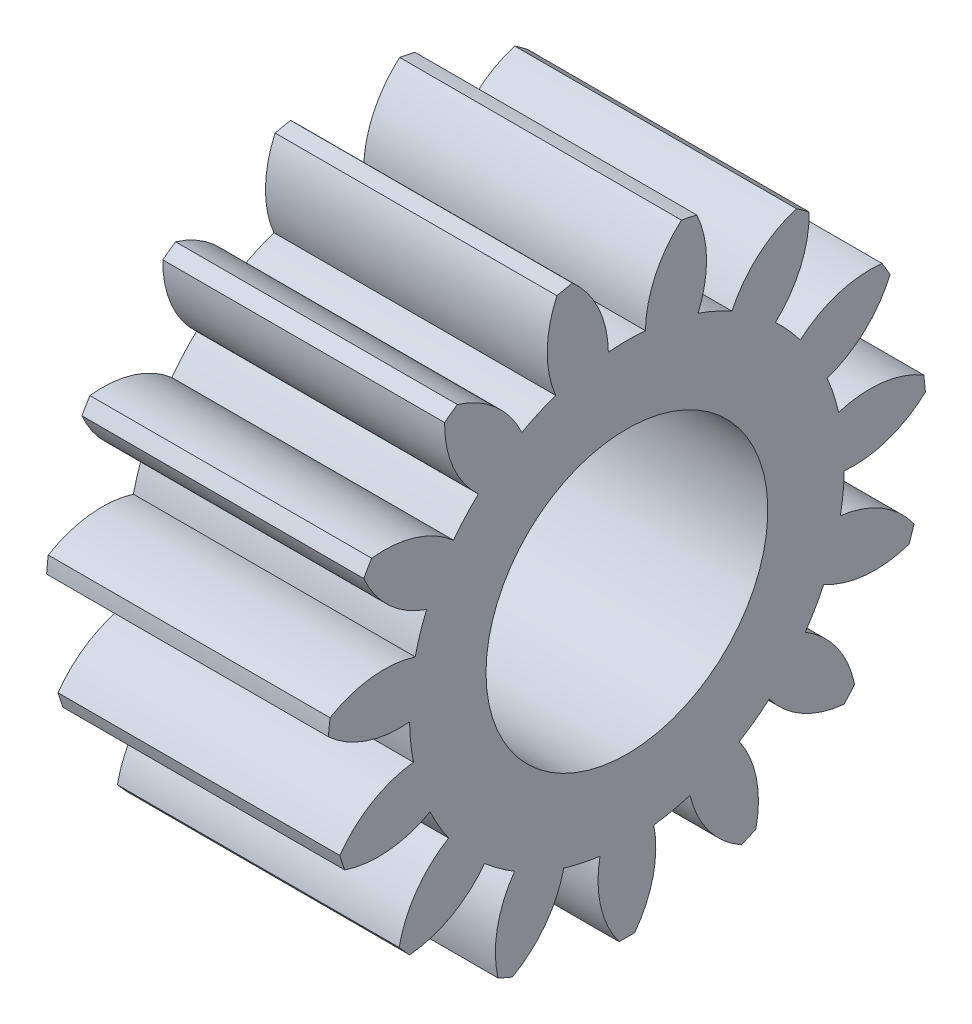
SolidWorks part; units mm, degrees
ref_plane "Plane1" through (0, 0, 0) normal (0, 0, 1) x (1, 0, 0)
ref_plane "Plane2" through (0, 0, 0) normal (0, 1, 0) x (1, 0, 0)
ref_plane "Plane3" through (0, 0, 0) normal (1, 0, 0) x (0, 0, -1)
sketch "HoldingSke" plane through (0, 0, 0) normal (0, 1, 0) x (1, 0, 0)
  line L0 (0, 0) -> (1570.209, -420.7362)
  line L1 (-15, 0) -> (100, 0) construction
  line L2 (0, 0) -> (-2.1039, 2.3779)
  line L3 (0, 0) -> (-11.863, 4.5341)
  line L4 (0, 0) -> (8.3417, 2.2352)
  line L5 (0, 0) -> (-47.5972, -17.7524)
  line L6 (0, 0) -> (-2.632, -1.7758)
  line L7 (-2.1039, 2.3779) -> (8.8308, 51.9871)
  line L8 (-76.2, 54.61) -> (-72.771, 54.61)
  line L9 (-71.009, 38.7566) -> (-53.1078, 45.2721)
  line L10 (-76.2, 71.12) -> (104.1128, 71.12)
  line L11 (0, 0) -> (-3.175, 0)
  line L12 (-76.2, 101.6) -> (-76.1858, 101.6)
  line L13 (24.9733, 27.94) -> (52.9518, 28.4284)
  line L14 (24.9733, 27.94) -> (25.0241, 27.9398)
  line L15 (24.9733, 27.94) -> (100.4021, 29.52)
  circle A0 centre (0, 0) radius 1.5875
  circle A1 centre (0, 0) radius 2.4495
  circle A2 centre (0, 0) radius 38.1
  circle A3 centre (0, 0) radius 1.5875
  dimension "MHD" = 4.899
  dimension "Hub_dia" = 76.2
  dimension "Bore" = 3.175
  dimension "MBD" = 3.175
  dimension "Num_teeth" = 15
  dimension "Pitch" = 1625.6
  dimension "Overall_len" = 50.8
  dimension "Show_teeth" = 15
  dimension "Thickness" = 3.175
  dimension "OAL" = 50.8001
  dimension "T_dim" = 3.429
  dimension "Ap" = 20
  dimension "H" = 19.05
  dimension "Pitch_radius" = 180.3128
  dimension "Width" = 3.175
  dimension "Backlash" = 0.0142
  dimension "Addendum_fac" = 1
  dimension "Dedendum_fac" = 1.2
  dimension "Clearance_fac" = 0.2
  dimension "Dedendum_add" = 0.0508
sketch "BasProSke" plane through (0, 0, 0) normal (0, 1, 0) x (1, 0, 0)
  line L0 (-10, 0) -> (60, 0) construction
  line L1 (0, 0) -> (0, 3.3734)
  line L2 (0, 0) -> (3.175, 0)
  line L3 (3.175, 0) -> (3.175, 3.3734)
  line L4 (3.175, 3.3734) -> (0, 3.3734)
  dimension "Thickness" = 3.175
  dimension "Diameter" = 6.7469
revolve "Base-Revolve" add sketch "BasProSke" angle 360 about L0
sketch "TooCutSke" plane through (0, 0, 0) normal (1, 0, 0) x (0, 0, -1)
  line L1 (0, 0) -> (0, 107) construction
  line L2 (0, 0) -> (-0.336, 2.9575) construction
  line L3 (0, 0) -> (-1.232, 5.796) construction
  line L4 (-0.336, 2.9575) -> (-0.616, 2.898) construction
  arc A0 (0.2088, 2.4406) -> (-0.2088, 2.4406) centre (0, 0) ccw
  arc A1 (0.6391, 3.3382) -> (-0.6391, 3.3382) centre (0, 0) ccw
  circle A2 centre (0, 0) radius 2.9766 construction
  circle A3 centre (0, 0) radius 2.7971 construction
  arc A4 (-0.2088, 2.4406) -> (-0.6391, 3.3382) centre (-1.3993, 2.4219) ccw
  arc A5 (0.6391, 3.3382) -> (0.2088, 2.4406) centre (1.3993, 2.4219) ccw
  dimension "Root_dia" = 4.899
  dimension "Overcut_dia" = 6.7977
  dimension "Pitch_dia" = 5.9531
  dimension "Base_dia" = 5.5941
  dimension "Flank_rad" = 1.1906
  dimension "Half_ang" = 12
  dimension "Half_CT" = 0.2862
extrude "ToothCut" cut sketch "TooCutSke" along normal through all
fillet "Breaks" [suppressed] radius 0.0079
fillet "RootFillets" [suppressed] radius 0.1302
pattern_circular "TeethCuts" count 15 every 24 about axis through (-10, 0, 0) along (1, 0, 0) of "ToothCut", "RootFillets", "Breaks"
sketch "HubNeaOneSke" plane through (0, 0, 0) normal (-1, 0, 0) x (0, 0, 1)
  circle A0 centre (0, 0) radius 2.4495
  dimension "Diameter" = 4.899
extrude "HubNearOne" [suppressed] add sketch "HubNeaOneSke" along normal blind 47.6251
sketch "HubNeaBotSke" plane through (0, 0, 0) normal (-1, 0, 0) x (0, 0, 1)
  circle A0 centre (0, 0) radius 2.4495
  dimension "Diameter" = 4.899
extrude "HubNearBoth" [suppressed] add sketch "HubNeaBotSke" along normal blind 23.8125
ref_plane "FarPln" through (3.175, 0, 0) normal (1, 0, 0) x (0, 0, -1)
sketch "HubFarSke" plane through (3.175, 0, 0) normal (1, 0, 0) x (0, 0, -1)
  circle A0 centre (0, 0) radius 2.4495
  dimension "Diameter" = 4.899
extrude "HubFar" [suppressed] add sketch "HubFarSke" along normal blind 23.8125
sketch "BorSke" plane through (0, 0, 0) normal (1, 0, 0) x (0, 0, -1)
  circle A0 centre (0, 0) radius 1.5875
  dimension "Diameter" = 3.175
extrude "Bore" cut sketch "BorSke" along normal mid plane 101.6001
sketch "KeySke" plane through (0, 0, 0) normal (1, 0, 0) x (0, 0, -1)
  line L0 (-0.127, 0) -> (-0.127, 1.8415)
  line L1 (-0.127, 1.8415) -> (0.127, 1.8415)
  line L2 (0.127, 1.8415) -> (0.127, 0)
  line L3 (0, 0) -> (0, 34) construction
  line L4 (-0.127, 0) -> (0.127, 0)
  dimension "Offset" = 1.8415
  dimension "Width" = 0.254
extrude "Keyway" [suppressed] cut sketch "KeySke" along normal mid plane 101.6001
pattern_circular "Keyway2" [suppressed] count 2 every 90 about axis through (-10, 0, 0) along (1, 0, 0)
equation "' \"Pitch@HoldingSke\" = 4"
equation "' \"Num_teeth@HoldingSke\" = 12"
equation "' \"Ap@HoldingSke\" =  20"
equation "' \"Ap@HoldingSke\" = 20"
equation "' \"Width@HoldingSke\" = 0.5"
equation "' \"Hub_dia@HoldingSke\"= 1"
equation "' \"Hub_dia@HoldingSke\" = 1"
equation "' \"Overall_len@HoldingSke\" = 1.0"
equation "' \"Bore@HoldingSke\" = 0.75"
equation "' \"T_dim@HoldingSke\" = 0.85"
equation "' \"Width@KeySke\" = 0.25"
equation "' \"Show_teeth@HoldingSke\" = 13"
equation "' \"Backlash@HoldingSke\" = 0.009"
equation "' \"Addendum_fac@HoldingSke\" = 1.0"
equation "' \"Dedendum_fac@HoldingSke\" = 1.25"
equation "' \"Dedendum_add@HoldingSke\" = 0.00005"
equation "' \"Clearance_fac@HoldingSke\" = 0.25"
equation "' \"Pitch@HoldingSke\" = 0.5"
equation "' \"Num_teeth@HoldingSke\" = 23"
equation "' \"Show_teeth@HoldingSke\" = 23"
equation "' \"Backlash@HoldingSke\" = 0.0375"
equation "\"Overcut_dia@TooCutSke\" = (\"Num_teeth@HoldingSke\" + 2 * \"Addendum_fac@HoldingSke\") / \"Pitch@HoldingSke\" + 0.002"
equation "\"Pitch_dia@TooCutSke\" = \"Num_teeth@HoldingSke\" / \"Pitch@HoldingSke\""
equation "\"Base_dia@TooCutSke\" = \"Num_teeth@HoldingSke\" / \"Pitch@HoldingSke\" * cos((\"Ap@HoldingSke\"  * 3.14159265 / 180))"
equation "\"Root_dia@TooCutSke\" = (\"Num_teeth@HoldingSke\" + 2) / \"Pitch@HoldingSke\" - 2 * (\"Addendum_fac@HoldingSke\" + \"Dedendum_fac@HoldingSke\") / \"Pitch@HoldingSke\" - \"Dedendum_add@HoldingSke\" * 2"
equation "\"Half_ang@TooCutSke\" = 180 / \"Num_teeth@HoldingSke\""
equation "\"Half_CT@TooCutSke\" = \"Num_teeth@HoldingSke\" / \"Pitch@HoldingSke\" * sin((3.14159265 / 2 / \"Num_teeth@HoldingSke\")) / 2 - 7 * \"Backlash@HoldingSke\" / 4"
equation "\"Flank_rad@TooCutSke\" = \"Num_teeth@HoldingSke\" / \"Pitch@HoldingSke\" / 5"
equation "\"Radius@RootFillets\" = \"Clearance_fac@HoldingSke\" / \"Pitch@HoldingSke\" + \"Dedendum_add@HoldingSke\""
equation "\"Break_rad@Breaks\" = 0.02 / \"Pitch@HoldingSke\""
equation "\"Thickness@HoldingSke\" = \"Width@HoldingSke\""
equation "\"OAL@HoldingSke\" = \"Thickness@HoldingSke\""
equation "\"MHD@HoldingSke\" = (\"Num_teeth@HoldingSke\" + 2) / \"Pitch@HoldingSke\" - 2 * (\"Addendum_fac@HoldingSke\" + \"Dedendum_fac@HoldingSke\")  / \"Pitch@HoldingSke\" - \"Dedendum_add@HoldingSke\" * 2"
equation "\"MBD@HoldingSke\" = (\"Num_teeth@HoldingSke\" + 2) / \"Pitch@HoldingSke\" - 2 * (\"Addendum_fac@HoldingSke\" + \"Dedendum_fac@HoldingSke\")  / \"Pitch@HoldingSke\" - \"Dedendum_add@HoldingSke\" * 2 - 0.002"
equation "\"MHD@HoldingSke\" = ((sgn( \"MHD@HoldingSke\" - \"Hub_dia@HoldingSke\" )-1)*( \"MHD@HoldingSke\" - \"Hub_dia@HoldingSke\" ))/-2+ \"Hub_dia@HoldingSke\""
equation "\"MBD@HoldingSke\" = ((sgn( \"MBD@HoldingSke\" - \"Bore@HoldingSke\" )-1)*( \"MBD@HoldingSke\" - \"Bore@HoldingSke\" ))/-2+ \"Bore@HoldingSke\""
equation "\"OAL@HoldingSke\" = ((sgn( \"OAL@HoldingSke\" - \"Overall_len@HoldingSke\" )+1)*( \"OAL@HoldingSke\" - \"Overall_len@HoldingSke\" ))/2 + \"Overall_len@HoldingSke\" + 0.000002"
equation "\"Num_teeth@TeethCuts\" = int( \"Show_teeth@HoldingSke\" ) + 1"
equation "\"Num_teeth@TeethCuts\" = ((sgn( \"Num_teeth@TeethCuts\" - \"Num_teeth@HoldingSke\" )-1)*( \"Num_teeth@TeethCuts\" - \"Num_teeth@HoldingSke\" ))/-2+ \"Num_teeth@HoldingSke\""
equation "\"Num_teeth@TeethCuts\" = ((sgn( \"Num_teeth@TeethCuts\" - 2.0)+1)*( \"Num_teeth@TeethCuts\" - 2.0))/2 +2.0"
equation "\"Angle@TeethCuts\" = 360.0 / \"Num_teeth@HoldingSke\""
equation "\"Diameter@BasProSke\" = (\"Num_teeth@HoldingSke\" + 2 * \"Addendum_fac@HoldingSke\") / \"Pitch@HoldingSke\""
equation "\"Thickness@BasProSke\"  = \"Thickness@HoldingSke\""
equation "' \"Fillet_rad@BasProSke\" =  \"Thickness@HoldingSke\" * 0.05"
equation "' \"Fillet_rad@BasProSke\" = \"Thickness@HoldingSke\" * 0.05"
equation "\"MHD@HoldingSke\" = ((sgn( \"MHD@HoldingSke\" - \"Root_dia@TooCutSke\" )-1)*( \"MHD@HoldingSke\" - \"Root_dia@TooCutSke\" ))/-2+ \"Root_dia@TooCutSke\""
equation "\"Diameter@HubNeaOneSke\" = \"MHD@HoldingSke\""
equation "\"Length@HubNearOne\" = \"OAL@HoldingSke\" - \"Thickness@BasProSke\""
equation "\"Diameter@HubNeaBotSke\" = \"MHD@HoldingSke\""
equation "\"Length@HubNearBoth\" = ( \"OAL@HoldingSke\" - \"Thickness@BasProSke\" ) / 2.0"
equation "\"Thickness@FarPln\" = \"Thickness@BasProSke\""
equation "\"Diameter@HubFarSke\" = \"MHD@HoldingSke\""
equation "\"Length@HubFar\" = ( \"OAL@HoldingSke\" - \"Thickness@BasProSke\" ) / 2.0"
equation "\"Diameter@BorSke\" = \"MBD@HoldingSke\""
equation "\"D1@Bore\" = \"OAL@HoldingSke\" * 2.0"
equation "\"D1@Keyway\" = \"OAL@HoldingSke\" * 2.0"
equation "\"Offset@KeySke\" = \"T_dim@HoldingSke\" - \"MBD@HoldingSke\" / 2.0"
